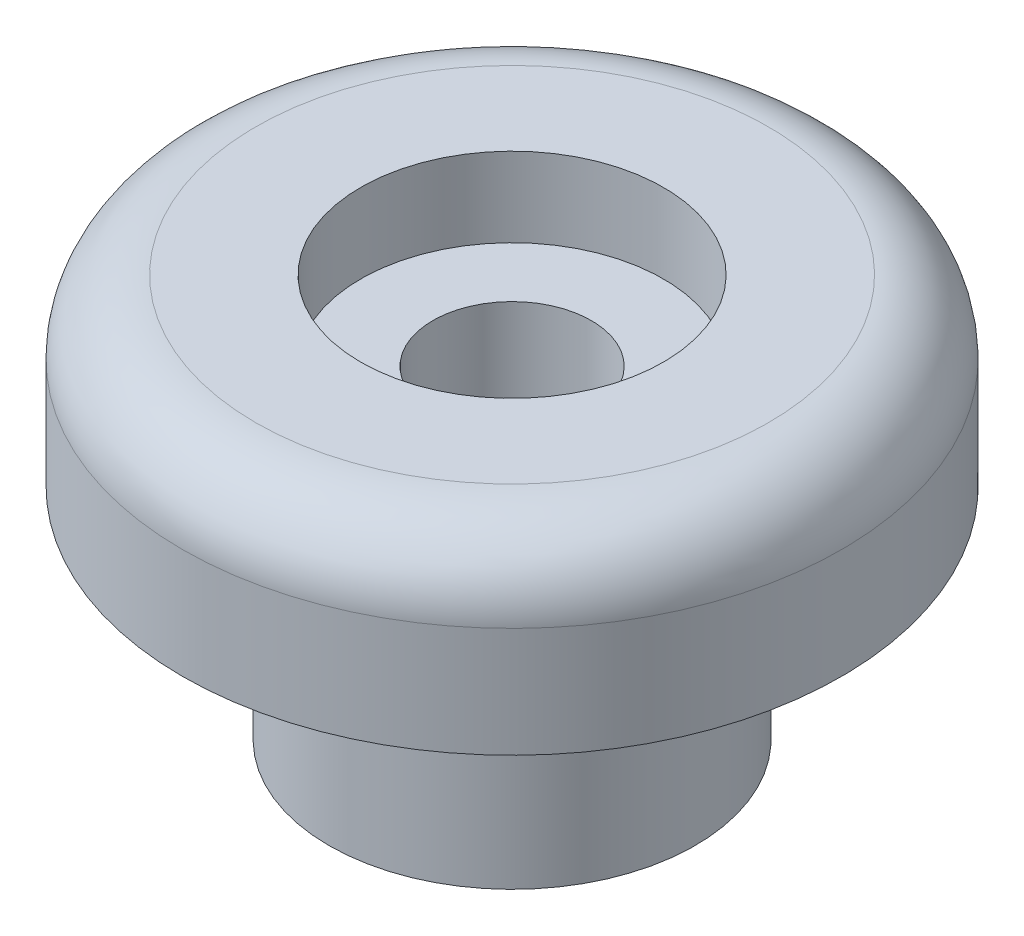
SolidWorks part; units mm, degrees
ref_plane "Front Plane" through (0, 0, 0) normal (0, 0, 1) x (1, 0, 0)
ref_plane "Top Plane" through (0, 0, 0) normal (0, 1, 0) x (1, 0, 0)
ref_plane "Right Plane" through (0, 0, 0) normal (1, 0, 0) x (0, 0, -1)
sketch "Sketch1" plane through (0, 0, 0) normal (0, 1, 0) x (1, 0, 0)
  circle A0 centre (0, 0) radius 3 construction
  circle A1 centre (0, 0) radius 6.35
  dimension "D1" = 6
  dimension "D2" = 12.7
extrude "Boss-Extrude1" add sketch "Sketch1" along normal blind 8.89
sketch "Sketch2" plane through (0, 8.89, 0) normal (0, 1, 0) x (1, 0, 0)
  circle A0 centre (0, 0) radius 11.43
  circle A1 centre (0, 0) radius 6.35
  circle A2 centre (0, 0) radius 6.35 construction
  dimension "D2" = 22.86
  dimension "D1" = 0
extrude "Boss-Extrude2" add sketch "Sketch2" along normal blind 5.08 and the other way blind 1.27
sketch "Sketch4" plane through (0, 13.97, 0) normal (0, 1, 0) x (1, 0, 0)
  circle A1 centre (0, 0) radius 11.43
  circle A2 centre (0, 0) radius 11.43 construction
  point P1 (0, 0)
  dimension "D1" = 0
hole_wizard "CBORE for M5 SBHCS1" positions "Sketch4" profile "Sketch6" counterbore size "M5" standard "ANSI Metric" end condition through all
sketch "Sketch6" plane through (0, 13.97, 0) normal (1, 0, 0) x (0, 0, 1)
  line L0 (0, 0) -> (0, 13.97)
  line L1 (0, 13.97) -> (2.75, 13.97)
  line L3 (2.75, 13.97) -> (2.75, 2.75)
  line L4 (2.75, 2.75) -> (5.25, 2.75)
  line L5 (5.25, 2.75) -> (5.25, 0)
  line L7 (5.25, 0) -> (0, 0)
  line L11 (0, -6.35) -> (0, 107.95) construction
  dimension "Thru Hole Dia." = 5.5
  dimension "Thru Hole Depth" = 13.97
  dimension "C'Bore Dia." = 10.5
  dimension "C'Bore Depth" = 2.75
fillet "Fillet1" radius 2.54 1 edges at (0, 13.97, 11.43)
